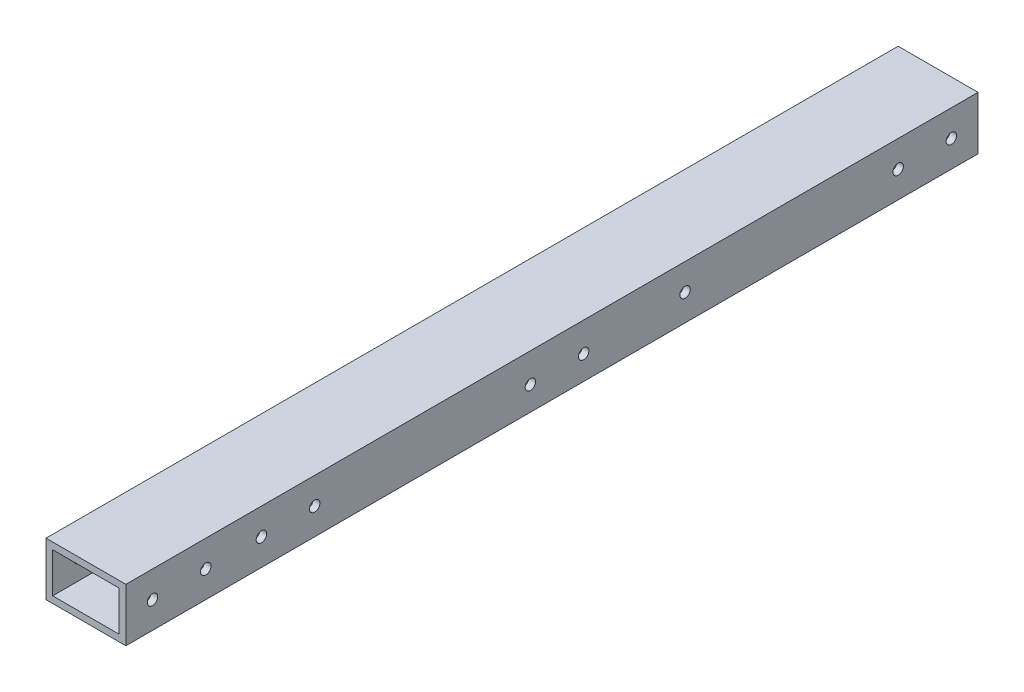
SolidWorks part; units mm, degrees
ref_plane "Front Plane" through (0, 0, 0) normal (0, 0, 1) x (1, 0, 0)
ref_plane "Top Plane" through (0, 0, 0) normal (0, 1, 0) x (1, 0, 0)
ref_plane "Right Plane" through (0, 0, 0) normal (1, 0, 0) x (0, 0, -1)
sketch "Sketch1" plane through (0, 0, 0) normal (0, 0, 1) x (1, 0, 0)
  line L0 (-15.875, 9.525) -> (15.875, 9.525)
  line L2 (-19.05, 12.7) -> (19.05, 12.7)
  line L3 (-19.05, 12.7) -> (-19.05, -12.7)
  line L4 (-19.05, -12.7) -> (19.05, -12.7)
  line L5 (19.05, 12.7) -> (19.05, -12.7)
  line L10 (15.875, 9.525) -> (15.875, -9.525)
  line L11 (-15.875, -9.525) -> (15.875, -9.525)
  line L12 (-15.875, 9.525) -> (-15.875, -9.525)
  point P12 (0, 12.7)
  point P14 (19.05, 0)
  dimension "Wall Thickness" = 3.175
  dimension "Outside Width" = 38.1
  dimension "Outside Height" = 25.4
  dimension "Inside Height" = 19.05
  dimension "Inside Width" = 31.75
sketch "Sketch2" plane through (0, 0, 0) normal (1, 0, 0) x (0, 0, -1)
  line L0 (317.5, 0) -> (-317.5, 0)
  point P4 (0, 0)
  point P7 (-317.5, 0)
  point P10 (317.5, 0)
  dimension "Length" = 635
sketch "Sketch3" plane through (0, 0, 0) normal (0, 0, 1) x (1, 0, 0)
  line L21 (19.05, 12.7) -> (-19.05, 12.7)
  line L22 (19.05, -12.7) -> (19.05, 12.7)
  line L23 (-19.05, -12.7) -> (19.05, -12.7)
  line L24 (-19.05, 12.7) -> (-19.05, -12.7)
  line L25 (19.05, 12.7) -> (-19.05, 12.7)
  line L26 (19.05, -12.7) -> (19.05, 12.7)
  line L27 (-19.05, -12.7) -> (19.05, -12.7)
  line L28 (-19.05, 12.7) -> (-19.05, -12.7)
  line L29 (15.875, 9.525) -> (-15.875, 9.525)
  line L30 (15.875, -9.525) -> (15.875, 9.525)
  line L31 (-15.875, -9.525) -> (15.875, -9.525)
  line L32 (-15.875, 9.525) -> (-15.875, -9.525)
  line L33 (15.875, 9.525) -> (-15.875, 9.525)
  line L34 (15.875, -9.525) -> (15.875, 9.525)
  line L35 (-15.875, -9.525) -> (15.875, -9.525)
  line L36 (-15.875, 9.525) -> (-15.875, -9.525)
  dimension "D1" = 0
  dimension "D2" = 0
extrude "Boss-Extrude1" add sketch "Sketch3" along normal up to vertex (317.5 mm away) and the other way up to vertex (317.5 mm away) up to point (0, 0, 317.5) other way up to point (0, 0, -317.5)
sketch "Drawing Reference" plane through (0, 0, 0) normal (1, 0, 0) x (0, 0, -1)
  line L0 (-317.5, 0) -> (317.5, 0) construction
  line L1 (0, -12.7) -> (0, 12.7) construction
  line L2 (-317.5, -12.7) -> (317.5, -12.7) construction
  line L5 (-317.5, 12.7) -> (317.5, 12.7) construction
  point P7 (-290.068, 0)
  point P8 (290.068, 0)
  dimension "D1" = 27.432
sketch "Sketch4" plane through (-19.05, 0, 0) normal (-1, 0, 0) x (0, 0, 1)
  line L3 (317.5, 12.7) -> (317.5, -12.7) construction
  line L4 (317.5, 0) -> (304.8, 0)
  line L5 (304.8, 0) -> (279.4, 0)
  line L6 (0, 0) -> (50.8, 0) construction
  line L7 (0, 0) -> (-50.8, 0) construction
  line L8 (-50.8, 0) -> (-76.2, 0) construction
  point P14 (304.8, 0)
  point P15 (279.4, 0)
hole_wizard "Mounting Holes" positions "Sketch11" profile "Sketch12" hole size "#10" standard "ANSI Inch" end condition through all
sketch "Sketch11" plane through (-19.05, 0, 0) normal (-1, 0, 0) x (0, 0, 1)
  point P6 (279.4, 0)
  point P9 (304.8, 0)
  point P12 (-76.2, 0)
sketch "Sketch12" plane through (-19.05, 0, 279.4) normal (0, 1, 0) x (0, 0, 1)
  line L0 (0, 0) -> (0, 38.1)
  line L1 (0, 38.1) -> (2.4892, 38.1)
  line L2 (2.4892, 38.1) -> (2.4892, 0)
  line L5 (2.4892, 0) -> (0, 0)
  line L11 (0, -6.35) -> (0, 107.95) construction
  dimension "Thru Hole Dia." = 4.9784
  dimension "Thru Hole Depth" = 38.1
hole_wizard "Rio Holes" positions "Sketch20" profile "Sketch21" hole size "#10" standard "ANSI Inch" end condition through all
sketch "Sketch20" plane through (-19.05, 0, 0) normal (-1, 0, 0) x (0, 0, 1)
  point P0 (-50.8, 0)
  point P3 (50.8, 0)
sketch "Sketch21" plane through (-19.05, 0, -50.8) normal (0, 1, 0) x (0, 0, 1)
  line L0 (0, 0) -> (0, 38.1)
  line L1 (0, 38.1) -> (2.4892, 38.1)
  line L2 (2.4892, 38.1) -> (2.4892, 0)
  line L5 (2.4892, 0) -> (0, 0)
  line L11 (0, -6.35) -> (0, 107.95) construction
  dimension "Thru Hole Dia." = 4.9784
  dimension "Thru Hole Depth" = 38.1
ref_plane "Plane1" through (0, 0, -88.9) normal (0, 0, -1) x (-1, 0, 0)
other "SurfaceCut1"
hole_wizard "#10 Clearance Hole1" positions "Sketch22" profile "Sketch23" hole size "#10" standard "ANSI Inch" end condition through all
sketch "Sketch22" plane through (19.05, 0, 0) normal (1, 0, 0) x (0, 0, -1)
  point P0 (-252.857, 0)
  point P3 (-227.457, 0)
  point P6 (-99.187, -1.2316)
  point P9 (-124.587, -1.2316)
sketch "Sketch23" plane through (19.05, 0, 252.857) normal (0, 1, 0) x (0, 0, -1)
  line L0 (0, 0) -> (0, 38.1)
  line L1 (0, 38.1) -> (2.4892, 38.1)
  line L2 (2.4892, 38.1) -> (2.4892, 0)
  line L5 (2.4892, 0) -> (0, 0)
  line L11 (0, -6.35) -> (0, 107.95) construction
  dimension "Thru Hole Dia." = 4.9784
  dimension "Thru Hole Depth" = 38.1
equation "\"D1@Drawing Reference\"=\"Outside Width@Sketch1\" * 0.72"
